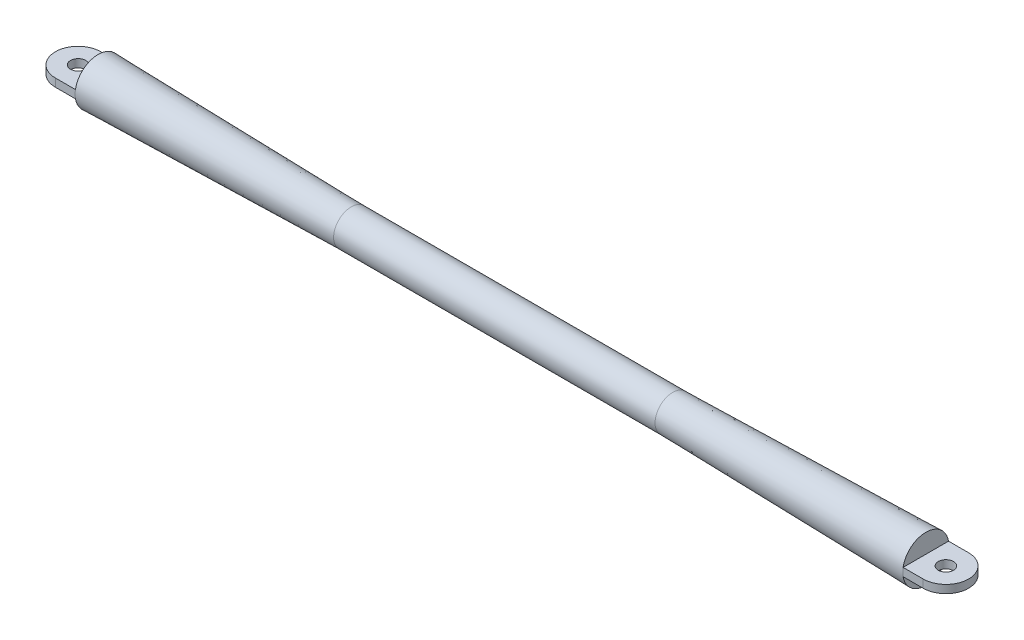
SolidWorks part; units mm, degrees
ref_plane "Front Plane" through (0, 0, 0) normal (0, 0, 1) x (1, 0, 0)
ref_plane "Top Plane" through (0, 0, 0) normal (0, 1, 0) x (1, 0, 0)
ref_plane "Right Plane" through (0, 0, 0) normal (1, 0, 0) x (0, 0, -1)
sketch "Sketch1" plane through (0, 0, 0) normal (0, 1, 0) x (1, 0, 0)
  line L0 (0, 0) -> (575, 0)
  line L1 (575, 0) -> (575, 30)
  line L2 (575, 30) -> (200, 22)
  line L3 (200, 22) -> (0, 22)
  line L4 (0, 22) -> (0, 0)
  dimension "D1" = 575
  dimension "D2" = 30
  dimension "D3" = 200
  dimension "D4" = 22
revolve "Revolve1" add sketch "Sketch1" angle 360 about L0
sketch "Sketch2" plane through (0, 0, 0) normal (0, 0, 1) x (1, 0, 0)
  line L0 (575, 0) -> (671.5861, 0) construction
  line L1 (575, -30) -> (575, 30) construction
  line L2 (515, -60.9406) -> (515, -5)
  line L3 (515, 60.9406) -> (643.6158, 60.9406)
  line L4 (515, 60.9406) -> (515, 5)
  line L5 (515, 5) -> (643.6158, 5)
  line L6 (643.6158, 60.9406) -> (643.6158, 5)
  line L7 (515, -5) -> (643.6158, -5)
  line L8 (643.6158, -60.9406) -> (643.6158, -5)
  line L9 (515, -60.9406) -> (643.6158, -60.9406)
  dimension "D1" = 10
  dimension "D2" = 60
extrude "Cut-Extrude1" cut sketch "Sketch2" against normal mid plane 1500
sketch "Sketch3" plane through (0, 5, 0) normal (0, 1, 0) x (1, 0, 0)
  line L0 (515, 28.2814) -> (540, 28.2814)
  line L1 (540, -28.2814) -> (515, -28.2814)
  line L2 (515, 28.2814) -> (515, 61.5602)
  line L3 (515, 61.5602) -> (604.6067, 61.5602)
  line L4 (604.6067, 61.5602) -> (604.6067, -67.5976)
  line L5 (604.6067, -67.5976) -> (515, -67.5976)
  line L6 (515, -67.5976) -> (515, -28.2814)
  arc A0 (540, 28.2814) -> (540, -28.2814) centre (540, 0) cw
  dimension "D1" = 25
extrude "Cut-Extrude2" cut sketch "Sketch3" against normal mid plane 1500
sketch "Sketch4" plane through (0, 5, 0) normal (0, 1, 0) x (1, 0, 0)
  circle A0 centre (540, 0) radius 9.5
  dimension "D1" = 19
extrude "Cut-Extrude3" cut sketch "Sketch4" against normal through all
mirror "Mirror2" about plane through (0, 0, -22) normal (1, 0, 0) of "Revolve1", "Cut-Extrude1", "Cut-Extrude2", "Cut-Extrude3"
